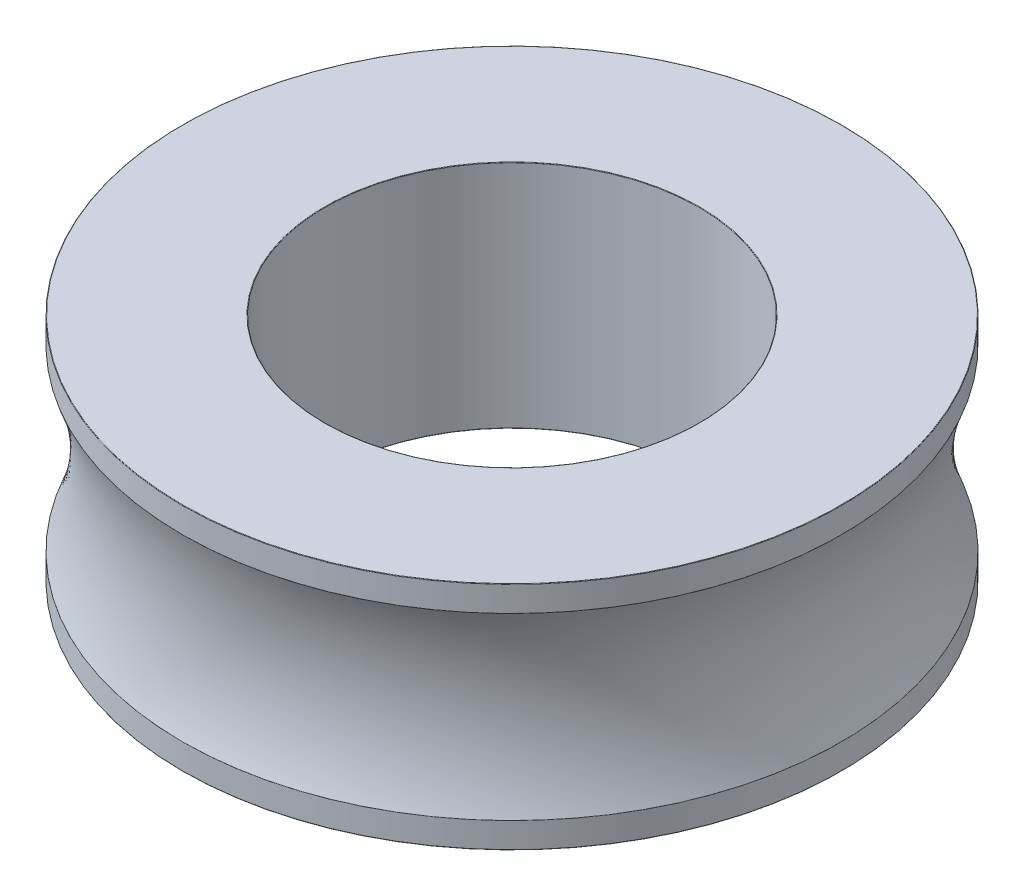
SolidWorks part; units mm, degrees
ref_plane "Front Plane" through (0, 0, 0) normal (0, 0, 1) x (1, 0, 0)
ref_plane "Top Plane" through (0, 0, 0) normal (0, 1, 0) x (1, 0, 0)
ref_plane "Right Plane" through (0, 0, 0) normal (1, 0, 0) x (0, 0, -1)
sketch "Sketch1" plane through (0, 0, 0) normal (0, 0, 1) x (1, 0, 0)
  line L0 (49.6637, 34.7384) -> (28.1875, 34.7384)
  line L1 (28.1875, 34.7384) -> (49.6637, 34.7384) construction
  line L2 (28.1875, 34.7384) -> (28.1875, 0) construction
  line L3 (28.1875, 0) -> (49.6637, 0) construction
  line L4 (49.6637, 34.7384) -> (49.6637, 0) construction
  line L5 (28.1875, 34.7384) -> (28.1875, 0)
  line L6 (28.1875, 0) -> (49.6637, 0)
  line L7 (49.6637, 0) -> (49.6637, 3.8598)
  line L8 (49.6637, 30.8786) -> (49.6637, 34.7384)
  line L9 (0, 0) -> (0, 7) construction
  arc A0 (49.6637, 30.8786) -> (49.6637, 3.8598) centre (82.8101, 17.3692) ccw
  dimension "D4" = 35.7937
  dimension "D1" = 34.7384
  dimension "D2" = 28.1875
  dimension "D3" = 21.4762
  dimension "D6" = 3.8598
revolve "Revolve1" add sketch "Sketch1" angle 360 about L9
fillet "Fillet1" radius 0.0716 6 edges at (0, 0, -28.1875) (0, 0, -49.6637) (0, 3.8598, -49.6637) (0, 30.8786, -49.6637) (0, 34.7384, -49.6637) (0, 34.7384, -28.1875)
equation "\"D1@Sketch1\"=((\"Upper_mount_wall_thickness\"*2)+\"Upper_Mount_largest_radius\"+83mm)/4.14814815"
equation "\"D2@Sketch1\"=\"Upper_Mount_largest_radius\"/(0.8*2)"
equation "\"D3@Sketch1\"=\"Upper_Mount_largest_radius\"/2.1"
equation "\"D6@Sketch1\"=((\"Upper_mount_wall_thickness\"*2)+\"Upper_Mount_largest_radius\"+83mm)/37.33333333333333333"
equation "\"D4@Sketch1\"=\"Upper_Mount_largest_radius\"/1.26"
equation "\"Upper_Mount_largest_radius\" =45.1"
equation "\"Upper_mount_wall_thickness\" =8"
equation "\"D1@Fillet1\"=\"Upper_Mount_largest_radius\"/630"
equation "\"Lower_Mount_piston_rod_length\" =298"
equation "\"Lower_Mount_piston_rod_radius\"\t=5.9628"
equation "\"Piston_orifice_dia\"=3.3145"
equation "\"Spring_inner_dia\" =131"
equation "\"Spring_wire_dia\" =7"
